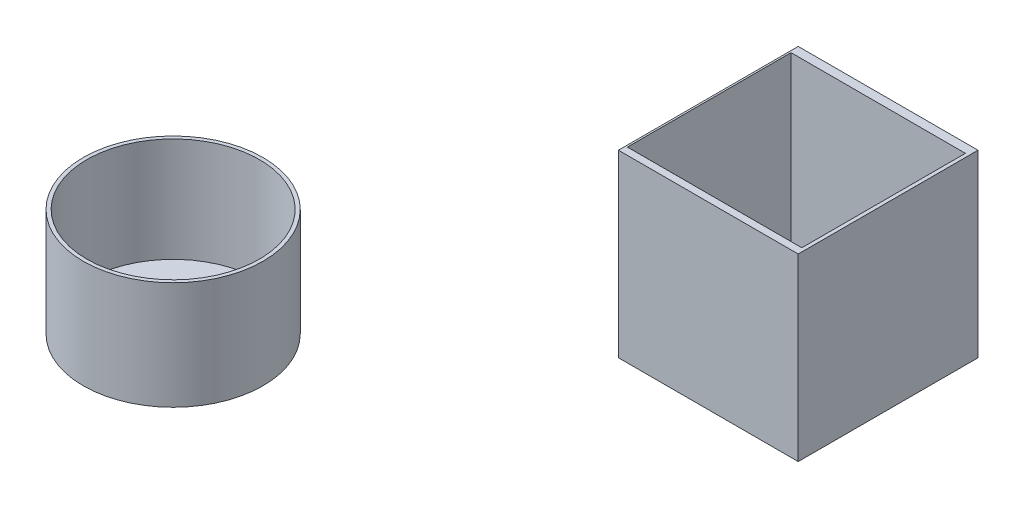
SolidWorks part; units mm, degrees
ref_plane "Front Plane" through (0, 0, 0) normal (0, 0, 1) x (1, 0, 0)
ref_plane "Top Plane" through (0, 0, 0) normal (0, 1, 0) x (1, 0, 0)
ref_plane "Right Plane" through (0, 0, 0) normal (1, 0, 0) x (0, 0, -1)
sketch "Sketch1" plane through (0, 0, 0) normal (0, 1, 0) x (1, 0, 0)
  circle A0 centre (0, 0) radius 50
extrude "Boss-Extrude1" add sketch "Sketch1" along normal blind 60
sketch "Sketch2" plane through (0, 0, 0) normal (0, 1, 0) x (1, 0, 0)
  line L1 (235.339, 112.342) -> (135.339, 112.342)
  line L2 (235.339, 112.342) -> (235.339, 212.342)
  line L3 (235.339, 212.342) -> (135.339, 212.342)
  line L4 (135.339, 112.342) -> (135.339, 212.342)
  dimension "D1" = 100
  dimension "D2" = 100
shell "Shell1" thickness 2
extrude "Boss-Extrude2" add sketch "Sketch2" along normal blind 100 separate body
shell "Shell2" thickness 2
